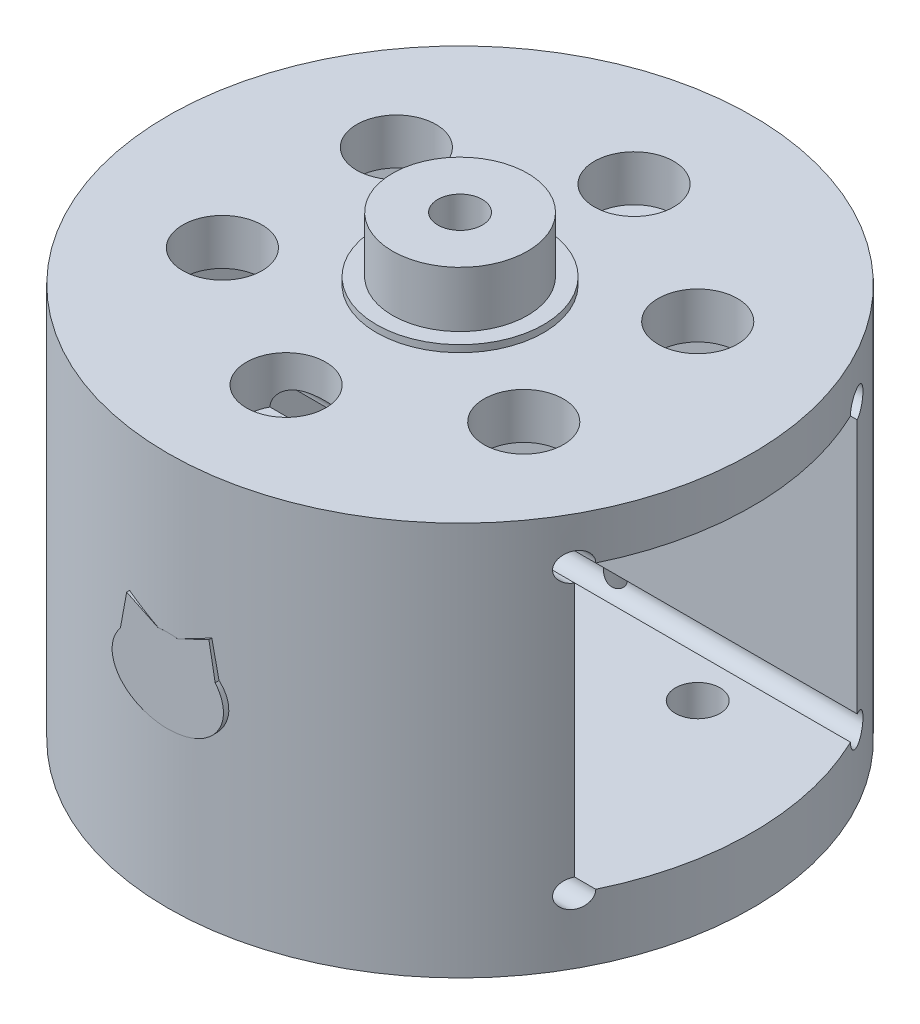
SolidWorks part; units mm, degrees
material "ABS"
ref_plane "前视基准面" through (0, 0, 0) normal (0, 0, 1) x (1, 0, 0)
ref_plane "上视基准面" through (0, 0, 0) normal (0, 1, 0) x (1, 0, 0)
ref_plane "右视基准面" through (0, 0, 0) normal (1, 0, 0) x (0, 0, -1)
other "Configuration Table"
sketch "草图1" plane through (0, 0, 0) normal (0, 1, 0) x (1, 0, 0)
  circle A0 centre (0, 0) radius 14.75
  dimension "D1" = 29.5
extrude "凸台-拉伸1" add sketch "草图1" along normal blind 4.2
sketch "草图2" plane through (0, 4.2, 0) normal (0, 1, 0) x (1, 0, 0)
  circle A0 centre (0, 0) radius 21
  dimension "D1" = 42
extrude "凸台-拉伸2" add sketch "草图2" along normal blind 25
sketch "草图4" plane through (0, 29.2, 0) normal (0, 1, 0) x (1, 0, 0)
  line L1 (-18, 10.15) -> (18, 10.15)
  line L2 (-18, 10.15) -> (-18, -10.15)
  line L3 (-18, -10.15) -> (18, -10.15)
  line L5 (-18, 10.15) -> (18, -10.15) construction
  line L6 (-18, -10.15) -> (18, 10.15) construction
  line L9 (18, 10.15) -> (116.2423, 10.15)
  line L10 (18, -10.15) -> (116.2423, -10.15)
  line L11 (116.2423, 10.15) -> (116.2423, -10.15)
  point P0 (0, 0)
  point P6 (-38.25, -10.9198)
  dimension "D1" = 20.3
  dimension "D2" = 18
extrude "切除-拉伸1" cut sketch "草图4" against normal blind 20.3
sketch "草图5" plane through (0, 0, 0) normal (0, -1, 0) x (1, 0, 0)
  circle A0 centre (0, 0) radius 12.5 construction
  circle A1 centre (0, 12.5) radius 1.6
  circle A2 centre (10.8253, 6.25) radius 1.6
  circle A3 centre (10.8253, -6.25) radius 1.6
  circle A4 centre (0, -12.5) radius 1.6
  circle A5 centre (-10.8253, -6.25) radius 1.6
  circle A6 centre (-10.8253, 6.25) radius 1.6
  dimension "D1" = 25
  dimension "D2" = 3.2
  dimension "D3" = 6
extrude "切除-拉伸2" cut sketch "草图5" against normal through all
sketch "草图6" plane through (0, 29.2, 0) normal (0, 1, 0) x (1, 0, 0)
  circle A0 centre (0, 0) radius 21
  circle A1 centre (0, 0) radius 21 construction
extrude "凸台-拉伸3" add sketch "草图6" along normal blind 3.3
sketch "草图8" plane through (0, 32.5, 0) normal (0, 1, 0) x (1, 0, 0)
  circle A0 centre (0, 0) radius 6
  dimension "D1" = 12
extrude "凸台-拉伸4" add sketch "草图8" along normal blind 0.5
sketch "草图9" plane through (0, 33, 0) normal (0, 1, 0) x (1, 0, 0)
  circle A0 centre (0, 0) radius 4.85
  dimension "D1" = 9.7
extrude "凸台-拉伸5" add sketch "草图9" along normal blind 4
sketch "草图7" plane through (0, 0, 0) normal (0, -1, 0) x (1, 0, 0)
  circle A0 centre (-10.8253, 6.25) radius 2.85
  circle A1 centre (10.8253, 6.25) radius 2.85
  circle A2 centre (10.8253, -6.25) radius 2.85
  circle A3 centre (-10.8253, -6.25) radius 2.85
  circle A4 centre (0, 12.5) radius 2.85
  circle A5 centre (0, -12.5) radius 2.85
  dimension "D1" = 5.7
extrude "切除-拉伸3" cut sketch "草图7" along normal up to surface (7.8 mm away) from surface at -37 up to face at (0.846, 29.2, 0) starting at face at (0, 37, 4.85)
sketch "草图10" plane through (0, 37, 0) normal (0, 1, 0) x (1, 0, 0)
  circle A0 centre (0, 0) radius 1.6
  dimension "D1" = 3.2
extrude "切除-拉伸4" cut sketch "草图10" against normal up to next and the other way through all
sketch "草图11" plane through (0, 37, 0) normal (0, 1, 0) x (1, 0, 0)
  line L1 (-3.15, 3.15) -> (3.15, 3.15)
  line L2 (-3.15, 3.15) -> (-3.15, -3.15)
  line L3 (-3.15, -3.15) -> (3.15, -3.15)
  line L4 (3.15, 3.15) -> (3.15, -3.15)
  line L5 (-3.15, 3.15) -> (3.15, -3.15) construction
  line L6 (-3.15, -3.15) -> (3.15, 3.15) construction
  point P0 (0, 0)
  dimension "D1" = 6.3
extrude "切除-拉伸5" cut sketch "草图11" against normal blind 6.3 from surface at -28.1 starting at face at (-10.8253, 8.9, 4.65)
sketch "草图14" plane through (0, 0, 0) normal (0, 0, 1) x (1, 0, 0)
  line L0 (0, 32.5) -> (0, 4.2) construction
  line L2 (-14.75, 4.2) -> (14.75, 4.2) construction
  line L3 (21, 32.5) -> (-21, 32.5) construction
  line L4 (0, 15.35) -> (0, 20.4205) construction
  line L5 (-2.9548, 22.3835) -> (-3.4049, 19.9244)
  line L6 (-2.9548, 22.3835) -> (-0.7, 21.3037)
  line L7 (2.9548, 22.3835) -> (0.7, 21.3037)
  line L8 (2.9548, 22.3835) -> (3.4049, 19.9244)
  ellipse E0 centre (0, 18.35) end of major axis (-4, 18.35) minor radius 3 (-3.4049, 19.9244) -> (3.4049, 19.9244) ccw
  ellipse E1 centre (0, 18.35) end of major axis (-4, 18.35) minor radius 3 (0.7, 21.3037) -> (-0.7, 21.3037) ccw
  dimension "D1" = 8
  dimension "D2" = 6
  dimension "D3" = 2.5
  dimension "D4" = 2.5
  dimension "D5" = 5
  dimension "D6" = 0.7
extrude "凸台-拉伸6" add sketch "草图14" along normal blind 1 from offset 20
sketch "草图15" plane through (-18, 0, 0) normal (1, 0, 0) x (0, 0, -1)
  circle A0 centre (-10.15, 29.2) radius 1
  circle A1 centre (10.15, 29.2) radius 1
  circle A2 centre (-10.15, 8.9) radius 1
  circle A3 centre (10.15, 8.9) radius 1
  dimension "D1" = 2
extrude "切除-拉伸6" cut sketch "草图15" along normal through all
